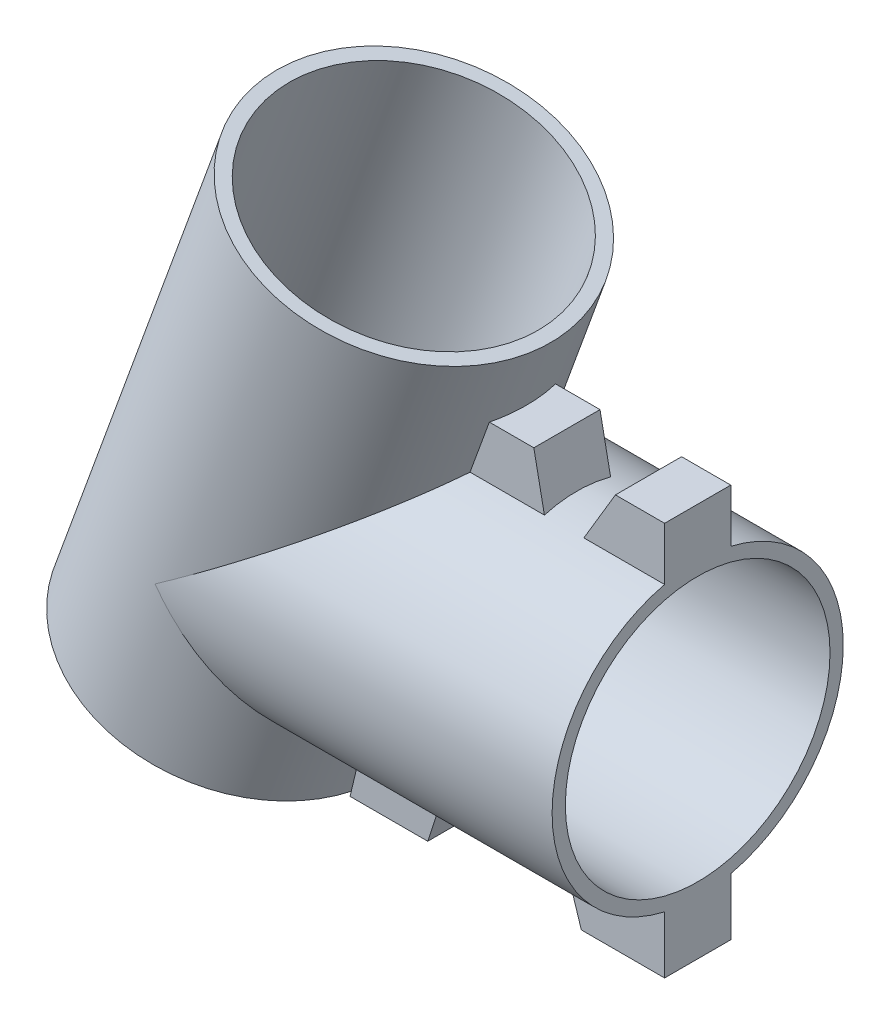
SolidWorks part; units mm, degrees
material "6061 合金"
ref_plane "前视基准面" through (0, 0, 0) normal (0, 0, 1) x (1, 0, 0)
ref_plane "上视基准面" through (0, 0, 0) normal (0, 1, 0) x (1, 0, 0)
ref_plane "右视基准面" through (0, 0, 0) normal (1, 0, 0) x (0, 0, -1)
sketch "草图1" plane through (0, 0, 0) normal (1, 0, 0) x (0, 0, -1)
  circle A0 centre (0, 0) radius 10
  circle A1 centre (0, 0) radius 11
  dimension "D1" = 20
  dimension "D2" = 1
extrude "凸台-拉伸1" add sketch "草图1" along normal blind 30
sketch "草图2" plane through (0, 0, 0) normal (0, 1, 0) x (1, 0, 0)
  line L0 (0, 11.5698) -> (0, -11.5545) construction
ref_plane "基准面1" through (0, 0, 0) normal (0.342, 0.9397, 0) x (0, 0, 1)
sketch "草图3" plane through (0, 0, 0) normal (0.342, 0.9397, 0) x (0, 0, 1)
  circle A0 centre (0, 0) radius 11
  circle A1 centre (0, 0) radius 10
  dimension "D1" = 22
  dimension "D2" = 20
extrude "凸台-拉伸2" add sketch "草图3" along normal blind 25 and the other way blind 12
sketch "草图4" plane through (8.5505, 23.4923, 0) normal (0.342, 0.9397, 0) x (0.9397, -0.342, 0)
  circle A0 centre (0, 0) radius 10
extrude "切除-拉伸1" cut sketch "草图4" against normal through all both and the other way through all
sketch "草图5" plane through (0, 0, 0) normal (0, 0, 1) x (1, 0, 0)
  line L0 (30, -15.0385) -> (30, -10.4652)
  line L2 (30, 14.7179) -> (26.2845, 14.7179)
  line L3 (16.3339, 14.7179) -> (14.6209, 10.2377)
  line L4 (0, 0) -> (15.7096, 11) construction
  line L5 (14.6209, 10.2377) -> (30, 10.2377)
  line L6 (30, -15.0385) -> (23.7098, -15.0385)
  line L7 (6.2324, -15.0385) -> (7.7023, -11) construction
  line L8 (6.2324, -15.0385) -> (7.3278, -10.4652)
  line L9 (0, 0) -> (7.7023, -11) construction
  line L10 (7.3278, -10.4652) -> (30, -10.4652)
  line L11 (30, 10.2377) -> (30, 14.7179)
  line L12 (30, -11) -> (30, 11) construction
  line L13 (12.1042, -15.0385) -> (13.5638, -10.5447)
  line L14 (13.5638, -10.5447) -> (22.268, -10.5447)
  line L15 (22.268, -10.5447) -> (23.7098, -15.0385)
  line L16 (20.1197, 14.7179) -> (20.9431, 10.5932)
  line L17 (20.9431, 10.5932) -> (23.8292, 10.5932)
  line L18 (23.8292, 10.5932) -> (26.2845, 14.7179)
  line L19 (20.1197, 14.7179) -> (16.3339, 14.7179)
  line L20 (12.1042, -15.0385) -> (6.2324, -15.0385)
  point P3 (30, 0)
extrude "凸台-拉伸3" add sketch "草图5" along normal mid plane 5
